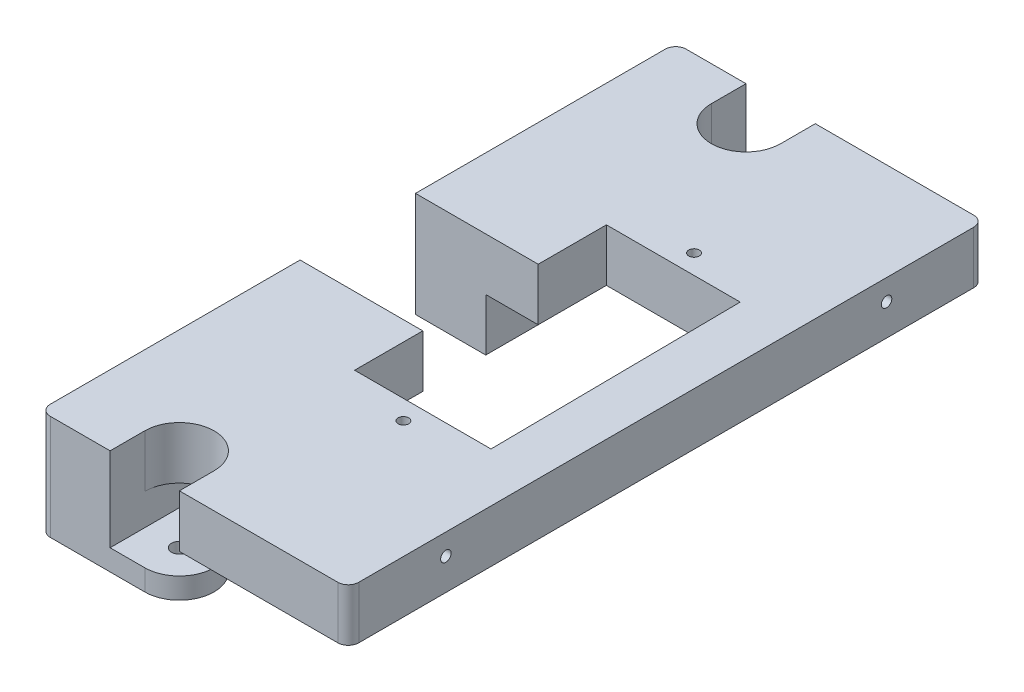
SolidWorks part; units mm, degrees
ref_plane "前视基准面" through (0, 0, 0) normal (0, 0, 1) x (1, 0, 0)
ref_plane "上视基准面" through (0, 0, 0) normal (0, 1, 0) x (1, 0, 0)
ref_plane "右视基准面" through (0, 0, 0) normal (1, 0, 0) x (0, 0, -1)
sketch "草图1" plane through (0, 0, 0) normal (0, 1, 0) x (1, 0, 0)
  line L0 (0, 0) -> (0, 54)
  line L1 (0, 50.697) -> (-2.303, 50.697)
  line L2 (0, 3.303) -> (-2.303, 3.303)
  line L3 (-3.303, 4.303) -> (-3.303, 49.697)
  line L4 (0, 57.303) -> (-9, 57.303)
  line L5 (-10, 56.303) -> (-10, -2.303)
  line L6 (-9, -3.303) -> (0, -3.303)
  circle A0 centre (0, 0) radius 1.5
  circle A1 centre (0, 54) radius 1.5
  arc A2 (0, 57.303) -> (0, 50.697) centre (0, 54) cw
  arc A3 (0, 3.303) -> (0, -3.303) centre (0, 0) cw
  arc A4 (-10, 56.303) -> (-9, 57.303) centre (-9, 56.303) cw
  arc A5 (-2.303, 50.697) -> (-3.303, 49.697) centre (-2.303, 49.697) ccw
  arc A6 (-9, -3.303) -> (-10, -2.303) centre (-9, -2.303) cw
  arc A7 (-2.303, 3.303) -> (-3.303, 4.303) centre (-2.303, 4.303) cw
  dimension "D1" = 1
extrude "凸台-拉伸1" add sketch "草图1" along normal blind 10
sketch "草图2" plane through (0, 10, 0) normal (0, 1, 0) x (1, 0, 0)
  line L1 (-3.303, -5.747) -> (5.3279, -5.747)
  line L2 (-3.303, -5.747) -> (-3.303, 59.5497)
  line L3 (-3.303, 59.5497) -> (5.3279, 59.5497)
  line L4 (5.3279, -5.747) -> (5.3279, 59.5497)
extrude "切除-拉伸1" cut sketch "草图2" against normal blind 8
sketch "草图3" plane through (-3.303, 0, 0) normal (1, 0, 0) x (0, 0, -1)
  line L0 (-3.303, 10) -> (-3.303, 5)
  line L1 (-3.303, 5) -> (57.303, 5)
  line L2 (57.303, 5) -> (57.303, 10)
  line L3 (57.303, 10) -> (-3.303, 10)
extrude "凸台-拉伸2" add sketch "草图3" along normal blind 15
sketch "草图4" plane through (0, 10, 0) normal (0, 1, 0) x (1, 0, 0)
  line L0 (10.697, -3.303) -> (-3.303, -3.303)
  line L1 (-3.303, -3.303) -> (-3.303, 57.303)
  line L2 (-3.303, 57.303) -> (10.697, 57.303)
  line L3 (11.697, 56.303) -> (11.697, -2.303)
  line L4 (10.697, -3.303) -> (11.697, -3.303)
  line L5 (11.697, -3.303) -> (11.697, 57.303)
  line L6 (11.697, 57.303) -> (10.697, 57.303)
  arc A0 (10.697, 57.303) -> (11.697, 56.303) centre (10.697, 56.303) cw
  arc A1 (10.697, -3.303) -> (11.697, -2.303) centre (10.697, -2.303) ccw
  point P9 (11.697, 57.303)
  point P12 (11.697, -3.303)
  line M7 (-9, -3.303) -> (11.697, -3.303)
  line M8 (11.697, -3.303) -> (11.697, 57.303)
  line M9 (11.697, 57.303) -> (-9, 57.303)
  dimension "D1" = 1
extrude "切除-拉伸2" cut sketch "草图4" against normal blind 15 contours A0 M9 M8 | A1 M7 M8
sketch "草图5" plane through (0, 5, 0) normal (0, -1, 0) x (1, 0, 0)
  line L0 (-3.303, -54) -> (-3.303, -57.303)
  line L1 (-3.303, -57.303) -> (3.303, -57.303)
  line L2 (3.303, -57.303) -> (3.303, -54)
  line L3 (-3.303, 0) -> (-3.303, 3.303)
  line L4 (-3.303, 3.303) -> (3.303, 3.303)
  line L5 (3.303, 3.303) -> (3.303, 0)
  arc A0 (0, 3.303) -> (-3.303, 0) centre (0, 0) cw
  arc A1 (0, -57.303) -> (0, -50.697) centre (0, -54) ccw
  arc A2 (0, -57.303) -> (-3.303, -54) centre (0, -54) ccw
  arc A3 (-3.303, -54) -> (3.303, -54) centre (0, -54) cw
  line M1 (-3.303, -57.303) -> (10.697, -57.303)
  line M5 (10.697, 3.303) -> (-3.303, 3.303)
  line M6 (-3.303, 3.303) -> (-3.303, -57.303)
extrude "切除-拉伸3" cut sketch "草图5" against normal blind 15 contours A0 L4 M6 | A0 L5 M5 | A1 A2 M6 M1 | A1 L1 L2
sketch "草图7" plane through (0, 5, 0) normal (0, -1, 0) x (-1, 0, 0)
  line L0 (3.303, 49.697) -> (3.303, 4.303)
  line L1 (3.303, 4.303) -> (3.303, 27)
  line L2 (3.303, 27) -> (3.303, 40)
  line L3 (3.303, 40) -> (-11.697, 40)
  line L4 (-11.697, 40) -> (-4.197, 40)
  line L5 (-4.197, 40) -> (-4.197, 27)
  line L6 (-4.197, 27) -> (2.303, 27)
  line L7 (2.303, 27) -> (2.303, 39)
  line L8 (2.303, 39) -> (-10.697, 39)
  line L9 (-10.697, 39) -> (-10.697, 15)
  line L10 (-10.697, 15) -> (2.303, 15)
  line L11 (2.303, 15) -> (2.303, 27)
extrude "切除-拉伸4" cut sketch "草图7" against normal blind 15 contours L7 L8 L5 L6 | L10 L11 L6 L5 L8 L9
sketch "草图8" plane through (11.697, 0, 0) normal (1, 0, 0) x (0, 0, -1)
  line L1 (-3.303, 10) -> (57.303, 10)
  line L2 (-3.303, 10) -> (-3.303, 5)
  line L3 (-3.303, 5) -> (57.303, 5)
  line L4 (57.303, 10) -> (57.303, 5)
extrude "凸台-拉伸3" add sketch "草图8" along normal blind 7.7 and the other way blind 1
sketch "草图10" plane through (0, 10, 0) normal (0, 1, 0) x (1, 0, 0)
  line L0 (18.397, -3.303) -> (19.397, -3.303)
  line L1 (3.303, -3.303) -> (18.397, -3.303)
  line L2 (3.303, -3.303) -> (3.303, 57.303)
  line L3 (3.303, 57.303) -> (18.397, 57.303)
  line L4 (19.397, -2.303) -> (19.397, 56.303)
  line L5 (19.397, -3.303) -> (19.397, -2.303)
  line L6 (18.397, 57.303) -> (19.397, 57.303)
  line L7 (19.397, 57.303) -> (19.397, 56.303)
  arc A0 (18.397, -3.303) -> (19.397, -2.303) centre (18.397, -2.303) ccw
  arc A1 (18.397, 57.303) -> (19.397, 56.303) centre (18.397, 56.303) cw
  point P10 (19.397, 57.303)
  line M11 (3.303, -3.303) -> (19.397, -3.303)
  line M12 (19.397, -3.303) -> (19.397, 57.303)
  line M13 (19.397, 57.303) -> (3.303, 57.303)
  dimension "D1" = 1
extrude "切除-拉伸5" cut sketch "草图10" against normal blind 7.7 contours A1 M13 M12 | A0 M11 M12
ref_plane "基准面1" through (-9, 10, -57.303) normal (0, -1, 0) x (-1, 0, 0)
sketch "草图12" plane through (0, 5, 0) normal (0, -1, 0) x (1, 0, 0)
  line L0 (18.397, -57.303) -> (17.397, -57.303)
  line L1 (17.397, -56.303) -> (17.397, 2.303)
  line L2 (17.397, 3.303) -> (19.397, 3.303)
  line L3 (19.397, -56.303) -> (19.397, 2.303)
  arc A0 (19.397, 2.303) -> (17.397, 2.303) centre (18.397, 2.303) ccw
  arc A1 (17.397, -56.303) -> (19.397, -56.303) centre (18.397, -56.303) ccw
  arc M6 (18.397, -57.303) -> (19.397, -56.303) centre (18.397, -56.303) ccw
  line M7 (19.397, -56.303) -> (19.397, 2.303)
  arc M8 (19.397, 2.303) -> (18.397, 3.303) centre (18.397, 2.303) ccw
extrude "凸台-拉伸4" add sketch "草图12" along normal blind 16 contours L1 A1 A0 M6 M7 M8
sketch "草图13" plane through (0, 10, 0) normal (0, 1, 0) x (1, 0, 0)
  line L0 (-2.303, 39) -> (10.697, 39)
  line L1 (10.697, 39) -> (4.197, 39)
  line L2 (4.197, 39) -> (-2.303, 39)
  line L3 (4.197, 39) -> (4.197, 40.85)
  line L4 (-2.303, 15) -> (10.697, 15)
  line L5 (10.697, 15) -> (4.197, 15)
  line L6 (4.197, 15) -> (4.197, 13.15)
  circle A0 centre (4.197, 13.15) radius 1.5
  circle A1 centre (4.197, 40.85) radius 1.5
extrude "切除-拉伸6" cut sketch "草图13" against normal blind 10.5
sketch "草图16" plane through (19.397, 0, 0) normal (1, 0, 0) x (0, 0, -1)
  line L0 (56.303, -11) -> (-2.303, -11)
  line L1 (-2.303, -11) -> (27, -11)
  line L2 (27, -11) -> (27, 10)
  line L3 (27, 10) -> (27, -0.5)
  line L4 (27, -0.5) -> (48, -0.5)
  line L5 (48, -0.5) -> (48, 8)
  line L6 (48, 8) -> (6, 8)
  line L7 (6, 8) -> (6, -0.5)
  line L8 (6, -0.5) -> (27, -0.5)
  line L9 (6, -0.5) -> (6, -9)
  line L10 (6, -9) -> (48, -9)
  line L11 (48, -9) -> (48, 8)
  circle A0 centre (6, 8) radius 0.5
  circle A1 centre (6, -9) radius 0.5
  circle A2 centre (48, -9) radius 0.5
  circle A3 centre (48, 8) radius 0.5
extrude "切除-拉伸7" cut sketch "草图16" against normal blind 2 contours L6 A0 L7 | L7 A0 L6 | L9 A1 L10 | L10 A1 L9 | L10 A2 L11 | L11 A2 L10 | L11 A3 L6 | L6 A3 L11
sketch "草图17" plane through (0, -11, 0) normal (0, -1, 0) x (1, 0, 0)
  line L1 (14.1027, -60.2648) -> (30.2904, -60.2648)
  line L2 (14.1027, -60.2648) -> (14.1027, 4.7289)
  line L3 (14.1027, 4.7289) -> (30.2904, 4.7289)
  line L4 (30.2904, -60.2648) -> (30.2904, 4.7289)
extrude "切除-拉伸8" cut sketch "草图17" against normal blind 16
sketch "草图18" plane through (0, 10, 0) normal (0, 1, 0) x (1, 0, 0)
  circle A0 centre (4.197, 13.15) radius 1.5
  circle A1 centre (4.197, 40.85) radius 1.5
  circle A2 centre (4.197, 13.15) radius 0.5
  circle A3 centre (4.197, 40.85) radius 0.5
extrude "凸台-拉伸5" add sketch "草图18" against normal blind 5
sketch "草图19" plane through (0, 0, 0) normal (0, -1, 0) x (1, 0, 0)
  circle A0 centre (0, -54) radius 0.75
  circle A1 centre (0, 0) radius 0.75
  circle A2 centre (0, 0) radius 1.5
  circle A3 centre (0, -54) radius 1.5
extrude "凸台-拉伸6" add sketch "草图19" against normal blind 2
sketch "草图20" plane through (0, 0, 0) normal (0, -1, 0) x (-1, 0, 0)
  line L0 (0, 54) -> (0, 0)
  line L1 (0, 0) -> (0, 27)
  line L2 (0, 27) -> (0, 21.5)
  line L3 (0, 27) -> (0, 32.5)
  line L4 (0, 32.5) -> (12.0569, 32.5)
  line L5 (12.0569, 32.5) -> (12.0569, 21.5)
  line L6 (12.0569, 21.5) -> (0, 21.5)
  line M4 (10, -2.303) -> (10, 56.303)
  line M10 (3.303, 49.697) -> (3.303, 4.303)
extrude "切除-拉伸9" cut sketch "草图20" against normal blind 15 contours L6 L4 M4 M10 | L6 L4 L0 M10 | L6 L5 L4 M4
sketch "草图21" plane through (0, 10, 0) normal (0, 1, 0) x (1, 0, 0)
  line L0 (10.697, 15) -> (14.697, 15)
  line L1 (14.697, 15) -> (14.4476, 39)
  line L2 (14.4476, 39) -> (10.697, 39)
  line L3 (10.697, 39) -> (10.697, 15)
extrude "切除-拉伸10" cut sketch "草图21" against normal blind 10
sketch "草图22" plane through (0, 10, 0) normal (0, 1, 0) x (1, 0, 0)
  line L0 (-2.303, 15) -> (1.697, 15)
  line L1 (-2.303, 15) -> (14.697, 15) construction
  line L2 (1.697, 15) -> (1.697, 21.5)
  line L3 (1.697, 21.5) -> (-2.303, 21.5)
  line L4 (-2.303, 21.5) -> (-2.303, 15)
  line L5 (-2.303, 39) -> (-2.303, 32.5)
  line L6 (-10, 32.5) -> (-2.303, 32.5) construction
  line L7 (-2.303, 39) -> (-2.303, 32.5) construction
  line L8 (-2.303, 32.5) -> (1.697, 32.5)
  line L9 (1.697, 32.5) -> (1.697, 39)
  line L10 (14.4476, 39) -> (-2.303, 39) construction
  line L11 (1.697, 39) -> (-2.303, 39)
extrude "凸台-拉伸7" add sketch "草图22" against normal blind 5
sketch "草图23" plane through (0, 10, 0) normal (0, 1, 0) x (1, 0, 0)
  line L0 (4.197, 13.15) -> (8.197, 13.15)
  line L1 (4.197, 40.85) -> (8.197, 40.85)
  circle A0 centre (8.197, 13.15) radius 0.5
  circle A1 centre (8.197, 40.85) radius 0.5
extrude "切除-拉伸11" cut sketch "草图23" against normal blind 5
sketch "草图24" plane through (0, 10, 0) normal (0, 1, 0) x (1, 0, 0)
  circle A0 centre (4.197, 13.15) radius 0.5
  circle A1 centre (4.197, 40.85) radius 0.5
extrude "凸台-拉伸8" add sketch "草图24" against normal blind 5
